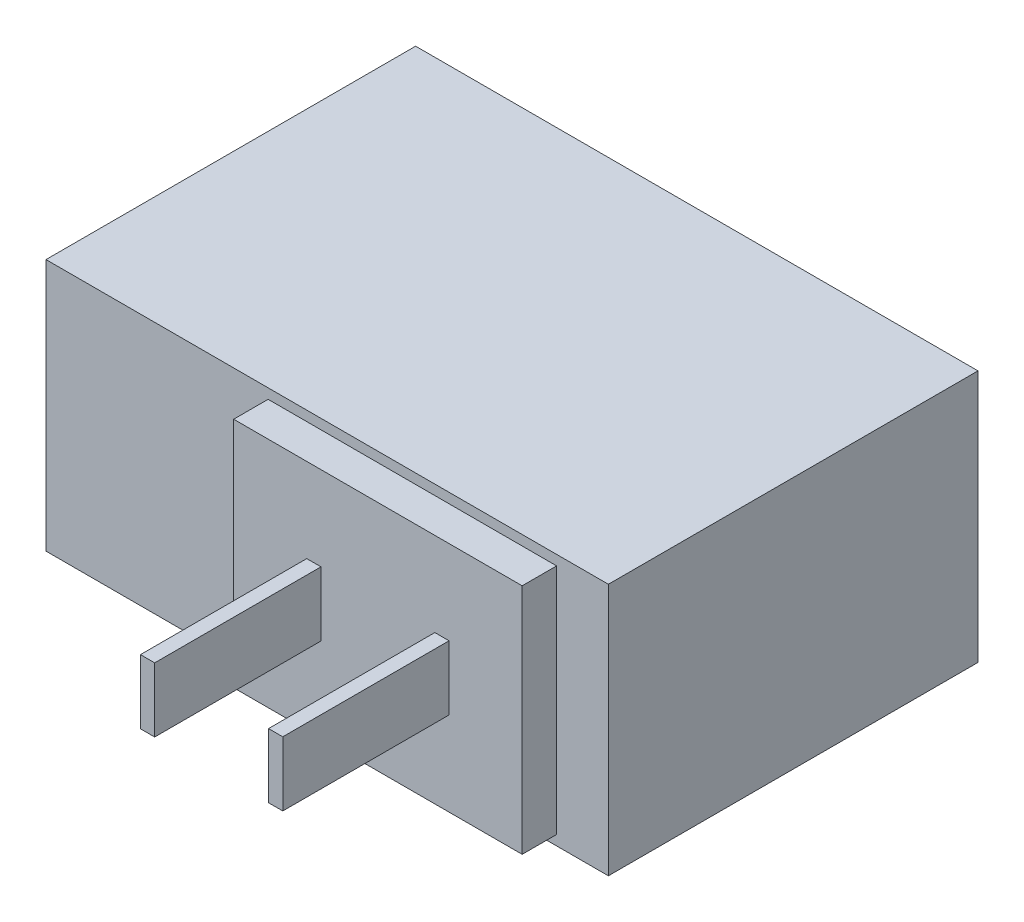
SolidWorks part; units mm, degrees
ref_plane "Front Plane" through (0, 0, 0) normal (0, 0, 1) x (1, 0, 0)
ref_plane "Top Plane" through (0, 0, 0) normal (0, 1, 0) x (1, 0, 0)
ref_plane "Right Plane" through (0, 0, 0) normal (1, 0, 0) x (0, 0, -1)
sketch "Sketch1" plane through (0, 0, 0) normal (0, 0, 1) x (1, 0, 0)
  line L1 (27.66, -12.42) -> (-27.66, -12.42)
  line L2 (27.66, -12.42) -> (27.66, 12.42)
  line L3 (27.66, 12.42) -> (-27.66, 12.42)
  line L4 (-27.66, -12.42) -> (-27.66, 12.42)
  line L5 (27.66, -12.42) -> (-27.66, 12.42) construction
  line L6 (27.66, 12.42) -> (-27.66, -12.42) construction
  point P0 (0, 0)
  dimension "D1" = 24.84
  dimension "D2" = 55.32
extrude "Boss-Extrude1" add sketch "Sketch1" along normal blind 36.36
sketch "Sketch2" plane through (0, 0, 36.36) normal (0, 0, 1) x (1, 0, 0)
  line L1 (22.57, 11.44) -> (-5.81, 11.44)
  line L2 (22.57, 11.44) -> (22.57, -11.44)
  line L3 (22.57, -11.44) -> (-5.81, -11.44)
  line L4 (-5.81, 11.44) -> (-5.81, -11.44)
  line L5 (27.66, -12.42) -> (27.66, 12.42) construction
  line L6 (27.66, 12.42) -> (22.57, 11.44) construction
  line L7 (27.66, -12.42) -> (22.57, -11.44) construction
  dimension "D2" = 5.09
  dimension "D3" = 22.88
  dimension "D4" = 28.38
extrude "Boss-Extrude2" add sketch "Sketch2" along normal blind 3.39
sketch "Sketch3" plane through (0, 0, 39.75) normal (0, 0, 1) x (1, 0, 0)
  line L0 (-5.81, 11.44) -> (1.38, 3.16) construction
  line L1 (13.98, 3.16) -> (15.38, 3.16)
  line L2 (13.98, 3.16) -> (13.98, -3.16)
  line L3 (13.98, -3.16) -> (15.38, -3.16)
  line L4 (15.38, 3.16) -> (15.38, -3.16)
  line L5 (1.38, 3.16) -> (2.78, 3.16)
  line L6 (1.38, 3.16) -> (1.38, -3.16)
  line L7 (1.38, -3.16) -> (2.78, -3.16)
  line L8 (2.78, 3.16) -> (2.78, -3.16)
  line L9 (22.57, 11.44) -> (15.38, 3.16) construction
  line L10 (-5.81, -11.44) -> (1.38, -3.16) construction
  line L11 (22.57, -11.44) -> (15.38, -3.16) construction
  dimension "D1" = 1.4
  dimension "D2" = 6.32
  dimension "D3" = 14
extrude "Boss-Extrude3" add sketch "Sketch3" along normal blind 16.36
